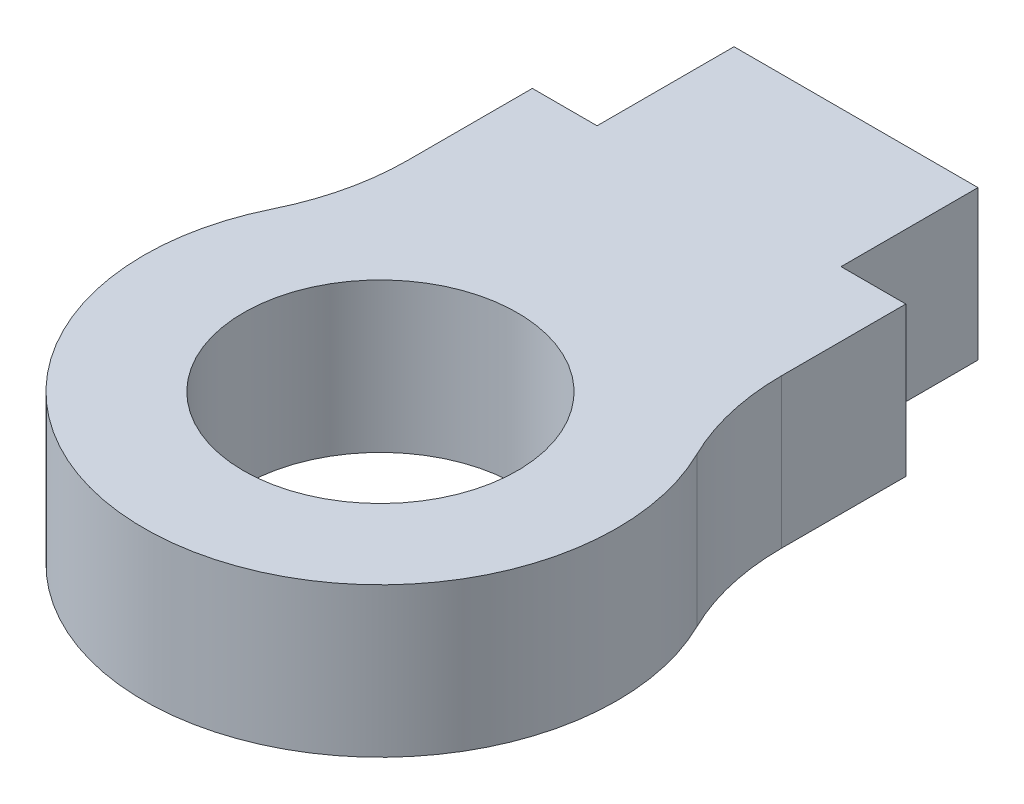
SolidWorks part; units mm, degrees
ref_plane "Front Plane" through (0, 0, 0) normal (0, 0, 1) x (1, 0, 0)
ref_plane "Top Plane" through (0, 0, 0) normal (0, 1, 0) x (1, 0, 0)
ref_plane "Right Plane" through (0, 0, 0) normal (1, 0, 0) x (0, 0, -1)
sketch "Sketch1" plane through (0, 0, 0) normal (0, 1, 0) x (1, 0, 0)
  line L0 (7.5, 8.6023) -> (7.5, 13.6023)
  line L1 (7.5, 13.6023) -> (4.9, 13.6023)
  line L2 (4.9, 13.6023) -> (4.9, 19.1023)
  line L3 (4.9, 19.1023) -> (-4.9, 19.1023)
  line L4 (-4.9, 19.1023) -> (-4.9, 13.6023)
  line L5 (-4.9, 13.6023) -> (-7.5, 13.6023)
  line L6 (-7.5, 13.6023) -> (-7.5, 8.6023)
  line L7 (0, 0) -> (0, 56.2399) construction
  circle A1 centre (0, 0) radius 5.5
  arc A2 (-8.5256, 4.1909) -> (8.5256, 4.1909) centre (0, 0) ccw
  arc A3 (-8.5256, 4.1909) -> (-7.5, 8.6023) centre (-17.5, 8.6023) ccw
  arc A4 (7.5, 8.6023) -> (8.5256, 4.1909) centre (17.5, 8.6023) ccw
  point P5 (0, 19.1023)
  dimension "D3" = 15
  dimension "D4" = 11
  dimension "D6" = 19
  dimension "D2" = 10
  dimension "D1" = 5.5
  dimension "D5" = 9.8
  dimension "D7" = 5
extrude "Boss-Extrude1" add sketch "Sketch1" along normal blind 6
